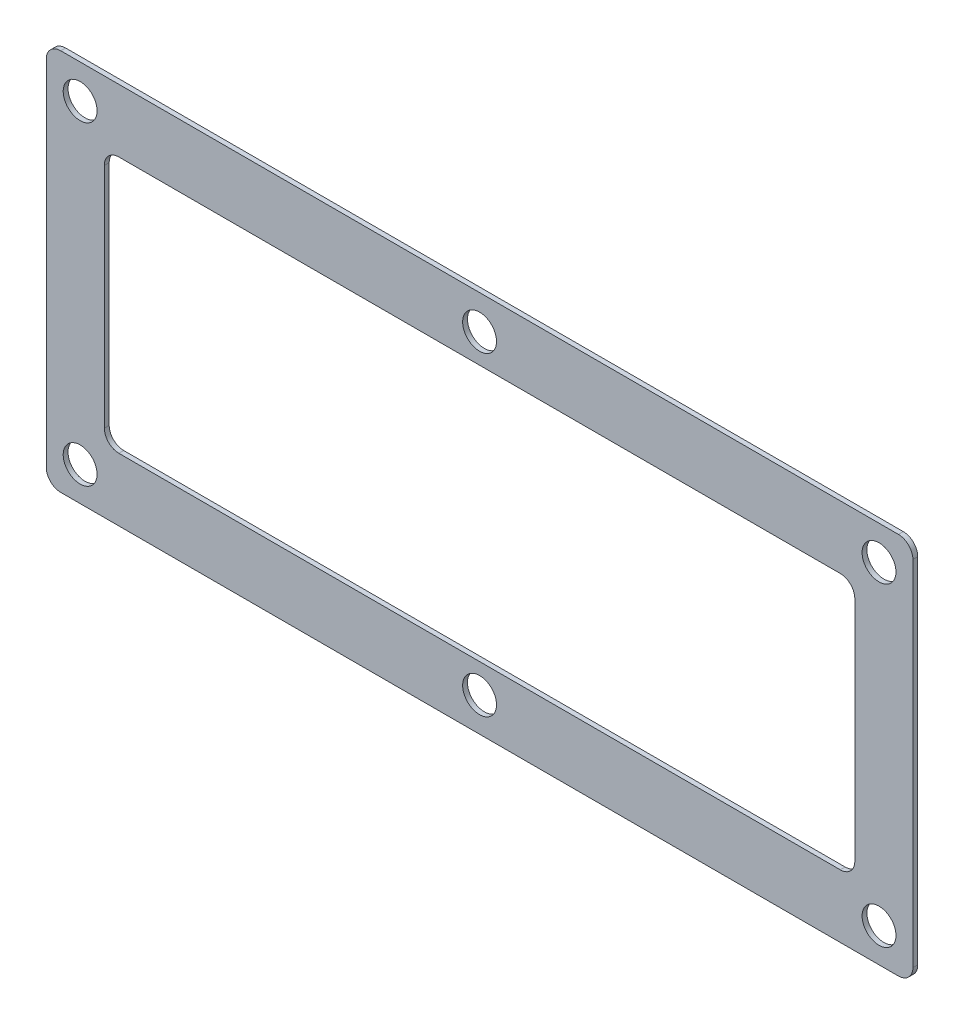
SolidWorks part; units mm, degrees
ref_plane "Front Plane" through (0, 0, 0) normal (0, 0, 1) x (1, 0, 0)
ref_plane "Top Plane" through (0, 0, 0) normal (0, 1, 0) x (1, 0, 0)
ref_plane "Right Plane" through (0, 0, 0) normal (1, 0, 0) x (0, 0, -1)
sketch "Sketch1" plane through (0, 0, 0) normal (0, 0, 1) x (1, 0, 0)
  line L6 (-89.5, -39.5) -> (89.5, -39.5)
  line L7 (-89.5, -39.5) -> (-89.5, 39.5)
  line L8 (-89.5, 39.5) -> (89.5, 39.5)
  line L9 (89.5, -39.5) -> (89.5, 39.5)
  line L10 (-89.5, -39.5) -> (89.5, 39.5) construction
  line L11 (-89.5, 39.5) -> (89.5, -39.5) construction
  point P0 (0, 0)
  dimension "D1" = 179
  dimension "D2" = 79
extrude "Boss-Extrude1" add sketch "Sketch1" along normal blind 1
fillet "Fillet1" radius 3 4 edges at (89.5, -39.5, 0.5) (-89.5, -39.5, 0.5) (-89.5, 39.5, 0.5) (89.5, 39.5, 0.5)
hole_wizard "Ø7.0 (7) Diameter Hole1" positions "Sketch2" profile "Sketch3" hole size "Ø7.0" standard "ISO" end condition through all
sketch "Sketch2" plane through (0, 0, 1) normal (0, 0, 1) x (1, 0, 0)
  line L0 (0, 39.5) -> (0, 32.5) construction
  line L1 (86.5, 39.5) -> (-86.5, 39.5) construction
  line L3 (-82.5, -32.5) -> (-82.5, 32.5) construction
  line L4 (-82.5, 32.5) -> (0, 32.5) construction
  line L5 (0, 32.5) -> (82.5, 32.5) construction
  line L6 (82.5, 32.5) -> (82.5, -32.5) construction
  line L7 (82.5, -32.5) -> (0, -32.5) construction
  line L8 (0, -32.5) -> (-82.5, -32.5) construction
  line L10 (-89.5, 36.5) -> (-89.5, -36.5) construction
  line L11 (-82.5, 0) -> (-89.5, 0) construction
  point P0 (0, 32.5)
  point P9 (-82.5, 32.5)
  point P11 (82.5, 32.5)
  point P13 (82.5, -32.5)
  point P15 (0, -32.5)
  point P17 (-82.5, -32.5)
  dimension "D1" = 7
  dimension "D2" = 7
sketch "Sketch3" plane through (0, 32.5, 1) normal (1, 0, 0) x (0, -1, 0)
  line L0 (0, 0) -> (0, 1)
  line L1 (0, 1) -> (3.5, 1)
  line L2 (3.5, 1) -> (3.5, 0)
  line L5 (3.5, 0) -> (0, 0)
  line L11 (0, -6.35) -> (0, 107.95) construction
  dimension "Thru Hole Dia." = 7
  dimension "Thru Hole Depth" = 1
ref_plane "Plane1" through (0, 0, 0) normal (-1, 0, 0) x (0, 0, 1)
ref_plane "Plane2" through (0, 0, 0) normal (0, 1, 0) x (1, 0, 0)
sketch "Sketch4" plane through (0, 0, 1) normal (0, 0, 1) x (1, 0, 0)
  line L0 (-89.5, 36.5) -> (-89.5, -36.5) construction
  line L1 (77.5, -26.5) -> (-77.5, -26.5)
  line L2 (77.5, -26.5) -> (77.5, 26.5)
  line L3 (77.5, 26.5) -> (-77.5, 26.5)
  line L4 (-77.5, -26.5) -> (-77.5, 26.5)
  line L5 (77.5, -26.5) -> (-77.5, 26.5) construction
  line L6 (77.5, 26.5) -> (-77.5, -26.5) construction
  line L7 (86.5, 39.5) -> (-86.5, 39.5) construction
  point P0 (0, 0)
  dimension "D1" = 12
  dimension "D2" = 13
extrude "Cut-Extrude1" cut sketch "Sketch4" against normal through all
fillet "Fillet2" radius 3 4 edges at (77.5, 26.5, 0.5) (77.5, -26.5, 0.5) (-77.5, -26.5, 0.5) (-77.5, 26.5, 0.5)
